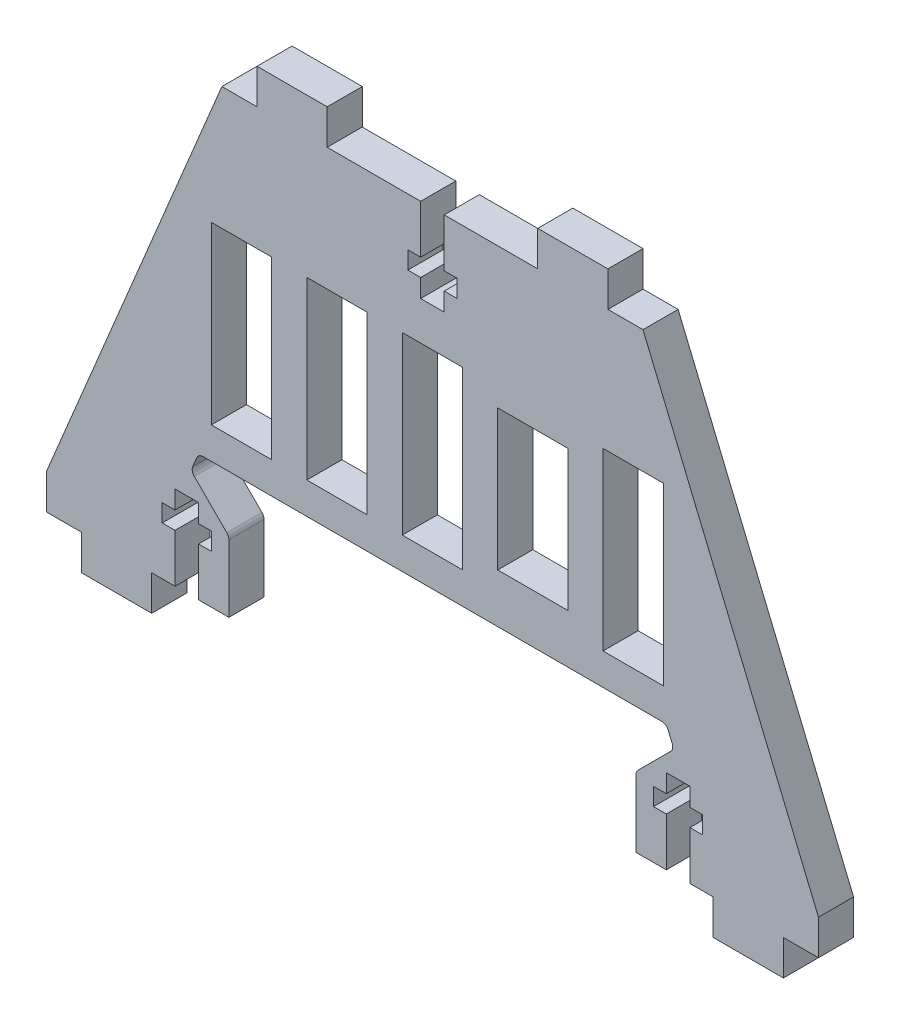
SolidWorks part; units mm, degrees
ref_plane "Front Plane" through (0, 0, 0) normal (0, 0, 1) x (1, 0, 0)
ref_plane "Top Plane" through (0, 0, 0) normal (0, 1, 0) x (1, 0, 0)
ref_plane "Right Plane" through (0, 0, 0) normal (1, 0, 0) x (0, 0, -1)
sketch "Sketch1" plane through (0, 0, 0) normal (0, 0, 1) x (1, 0, 0)
  line L1 (-69.85, 41.275) -> (69.85, 41.275)
  line L2 (-69.85, 41.275) -> (-69.85, -41.275)
  line L3 (-69.85, -41.275) -> (69.85, -41.275)
  line L4 (69.85, 41.275) -> (69.85, -41.275)
  line L5 (-69.85, 41.275) -> (69.85, -41.275) construction
  line L6 (-69.85, -41.275) -> (69.85, 41.275) construction
  point P0 (0, 0)
  dimension "D1" = 82.55
  dimension "D2" = 139.7
extrude "Boss-Extrude1" add sketch "Sketch1" along normal blind 6.35
sketch "Sketch2" plane through (0, 0, 0) normal (0, 0, -1) x (-1, 0, 0)
  line L0 (69.85, -41.275) -> (-69.85, -41.275) construction
  line L1 (-63.5, -41.275) -> (-50.8, -41.275)
  line L2 (-63.5, -41.275) -> (-63.5, -47.625)
  line L3 (-63.5, -47.625) -> (-50.8, -47.625)
  line L4 (-50.8, -41.275) -> (-50.8, -47.625)
  line L5 (-69.85, -41.275) -> (-69.85, 41.275) construction
  line L6 (-69.85, 41.275) -> (69.85, 41.275) construction
  line L7 (-31.75, 41.275) -> (-19.05, 41.275)
  line L8 (-31.75, 41.275) -> (-31.75, 47.625)
  line L9 (-31.75, 47.625) -> (-19.05, 47.625)
  line L10 (-19.05, 41.275) -> (-19.05, 47.625)
  dimension "D1" = 6.35
  dimension "D2" = 12.7
  dimension "D3" = 6.35
  dimension "D4" = 6.35
  dimension "D5" = 12.7
  dimension "D6" = 38.1
extrude "Boss-Extrude2" add sketch "Sketch2" against normal blind 6.35
sketch "Sketch3" plane through (0, 0, 0) normal (0, 0, -1) x (-1, 0, 0)
  line L1 (-46.5836, -41.275) -> (-46.5836, -32.512)
  line L2 (69.85, -41.275) -> (-50.8, -41.275) construction
  line L3 (-46.5836, -32.512) -> (-48.895, -32.512)
  line L4 (-48.895, -32.512) -> (-48.895, -29.337)
  line L5 (-48.895, -29.337) -> (-46.5836, -29.337)
  line L6 (-46.5836, -29.337) -> (-46.5836, -26.035)
  line L7 (-46.5836, -26.035) -> (-42.3164, -26.035)
  line L8 (-44.45, -26.035) -> (-44.45, -41.275) construction
  line L9 (-42.3164, -41.275) -> (-46.5836, -41.275)
  line L10 (-63.5, -47.625) -> (-50.8, -47.625) construction
  line L11 (-42.3164, -29.337) -> (-42.3164, -26.035)
  line L12 (-40.005, -29.337) -> (-42.3164, -29.337)
  line L13 (-40.005, -32.512) -> (-40.005, -29.337)
  line L14 (-42.3164, -32.512) -> (-40.005, -32.512)
  line L15 (-42.3164, -41.275) -> (-42.3164, -32.512)
  line L16 (-50.8, -47.625) -> (-50.8, -41.275) construction
  dimension "D1" = 21.59
  dimension "D2" = 3.302
  dimension "D3" = 3.175
  dimension "D4" = 4.2672
  dimension "D5" = 4.445
  dimension "D6" = 6.35
extrude "Cut-Extrude1" cut sketch "Sketch3" against normal blind 6.35
sketch "Sketch7" plane through (0, 0, 0) normal (0, 0, -1) x (-1, 0, 0)
  line L0 (-38.1, 41.275) -> (-69.85, -34.925)
  line L1 (-69.85, 41.275) -> (-31.75, 41.275) construction
  line L2 (-69.85, -41.275) -> (-69.85, 41.275) construction
  line L3 (-69.85, -34.925) -> (-69.85, 41.275)
  line L4 (-69.85, 41.275) -> (-38.1, 41.275)
  line L5 (-31.75, 47.625) -> (-31.75, 41.275) construction
  dimension "D1" = 6.35
  dimension "D2" = 6.35
extrude "Cut-Extrude8" cut sketch "Sketch7" against normal blind 6.35
mirror "Mirror2" about plane through (0, 0, 0) normal (1, 0, 0) of "Cut-Extrude8", "Boss-Extrude2"
mirror "Mirror4" about plane through (0, 0, 0) normal (1, 0, 0) of "Cut-Extrude1"
sketch "Sketch4" plane through (0, 0, 0) normal (0, 0, -1) x (-1, 0, 0)
  line L0 (0, 41.275) -> (0, 0) construction
  line L2 (2.1336, 41.275) -> (-2.1336, 41.275)
  line L3 (-2.1336, 41.275) -> (-2.1336, 32.512)
  line L4 (-2.1336, 32.512) -> (-4.445, 32.512)
  line L5 (-4.445, 32.512) -> (-4.445, 29.337)
  line L6 (-4.445, 29.337) -> (-2.1336, 29.337)
  line L7 (-2.1336, 29.337) -> (-2.1336, 26.035)
  line L8 (-2.1336, 26.035) -> (2.1336, 26.035)
  line L10 (2.1336, 29.337) -> (2.1336, 26.035)
  line L11 (4.445, 29.337) -> (2.1336, 29.337)
  line L12 (4.445, 32.512) -> (4.445, 29.337)
  line L13 (2.1336, 32.512) -> (4.445, 32.512)
  line L14 (2.1336, 41.275) -> (2.1336, 32.512)
  line L15 (-19.05, 47.625) -> (-31.75, 47.625) construction
  line L16 (-19.05, 41.275) -> (19.05, 41.275) construction
  point P15 (0, 26.035)
  dimension "D1" = 2.1336
  dimension "D2" = 4.445
  dimension "D3" = 21.59
  dimension "D4" = 3.302
  dimension "D5" = 3.175
extrude "Cut-Extrude2" cut sketch "Sketch4" against normal blind 6.35
sketch "Sketch8" plane through (0, 0, 6.35) normal (0, 0, 1) x (1, 0, 0)
  line L0 (-36.83, -28.575) -> (-43.7029, -21.7021)
  line L1 (36.83, -28.575) -> (43.7029, -21.7021)
  line L6 (-69.85, -34.925) -> (-38.1, 41.275) construction
  line L8 (69.85, -34.925) -> (38.1, 41.275) construction
  line L9 (-42.3164, -41.275) -> (42.3164, -41.275) construction
  line L10 (-69.85, -34.925) -> (-38.1, 41.275) construction
  line L11 (-36.83, -28.575) -> (-36.83, -41.275)
  line L12 (69.85, -34.925) -> (38.1, 41.275) construction
  line L13 (-36.83, -41.275) -> (36.83, -41.275)
  line L14 (-43.7029, -21.7021) -> (-42.3333, -18.415)
  line L15 (-42.3333, -18.415) -> (42.3333, -18.415)
  line L16 (2.1336, 26.035) -> (-2.1336, 26.035) construction
  line L17 (-52.2654, -42.2519) -> (-20.5154, 33.9481) construction
  line L18 (52.2654, -42.2519) -> (20.5154, 33.9481) construction
  line L19 (36.83, -28.575) -> (36.83, -41.275)
  line L20 (43.7029, -21.7021) -> (42.3333, -18.415)
  line L22 (40.005, -32.512) -> (40.005, -29.337) construction
  line L23 (-40.005, -32.512) -> (-40.005, -29.337) construction
  point P16 (40.005, -30.9245)
  dimension "D3" = 44.45
  dimension "D4" = 3.175
  dimension "D5" = 3.175
  dimension "D8" = 12.7
  dimension "D9" = 225
  dimension "D1" = 19.05
  dimension "D2" = 19.05
extrude "Cut-Extrude9" cut sketch "Sketch8" against normal through all and the other way through all
fillet "Fillet1" radius 1.27 6 edges at (36.83, -28.575, 3.175) (43.7029, -21.7021, 3.175) (42.3333, -18.415, 3.175) (-42.3333, -18.415, 3.175) (-43.7029, -21.7021, 3.175) (-36.83, -28.575, 3.175)
sketch "Sketch9" plane through (0, 0, 6.35) normal (0, 0, 1) x (1, 0, 0)
  line L0 (0, 26.035) -> (0, -18.415) construction
  line L1 (2.1336, 26.035) -> (-2.1336, 26.035) construction
  line L2 (41.4867, -18.415) -> (-41.4867, -18.415) construction
  line L3 (-53.975, 3.175) -> (53.975, 3.175) construction
  line L4 (-69.85, -34.925) -> (-38.1, 41.275) construction
  line L5 (69.85, -34.925) -> (38.1, 41.275) construction
  line L6 (-5.461, 19.05) -> (5.461, 19.05)
  line L7 (-40.005, 19.05) -> (-29.083, 19.05)
  line L8 (-40.005, 19.05) -> (-40.005, -12.7)
  line L9 (-40.005, -12.7) -> (-29.083, -12.7)
  line L10 (-29.083, 19.05) -> (-29.083, -12.7)
  line L11 (-22.733, 19.05) -> (-11.811, 19.05)
  line L12 (-22.733, 19.05) -> (-22.733, -12.7)
  line L13 (-22.733, -12.7) -> (-11.811, -12.7)
  line L14 (-11.811, 19.05) -> (-11.811, -12.7)
  line L15 (-5.461, 19.05) -> (-5.461, -12.7)
  line L16 (-5.461, -12.7) -> (5.461, -12.7)
  line L17 (5.461, 19.05) -> (5.461, -12.7)
  line L18 (30.861, 19.05) -> (41.783, 19.05)
  line L19 (30.861, 19.05) -> (30.861, -12.7)
  line L20 (30.861, -12.7) -> (41.783, -12.7)
  line L21 (41.783, 19.05) -> (41.783, -12.7)
  line L23 (11.811, 15.875) -> (24.511, 15.875)
  line L24 (11.811, 15.875) -> (11.811, -9.525)
  line L25 (11.811, -9.525) -> (24.511, -9.525)
  line L26 (24.511, 15.875) -> (24.511, -9.525)
  dimension "D1" = 10.922
  dimension "D2" = 31.75
  dimension "D3" = 10.922
  dimension "D4" = 10.922
  dimension "D5" = 31.75
  dimension "D6" = 6.35
  dimension "D7" = 10.922
  dimension "D8" = 6.35
  dimension "D9" = 12.7
  dimension "D10" = 25.4
  dimension "D11" = 6.35
  dimension "D12" = 6.35
  dimension "D13" = 31.75
  dimension "D14" = 31.75
extrude "Cut-Extrude10" cut sketch "Sketch9" against normal blind 6.35
